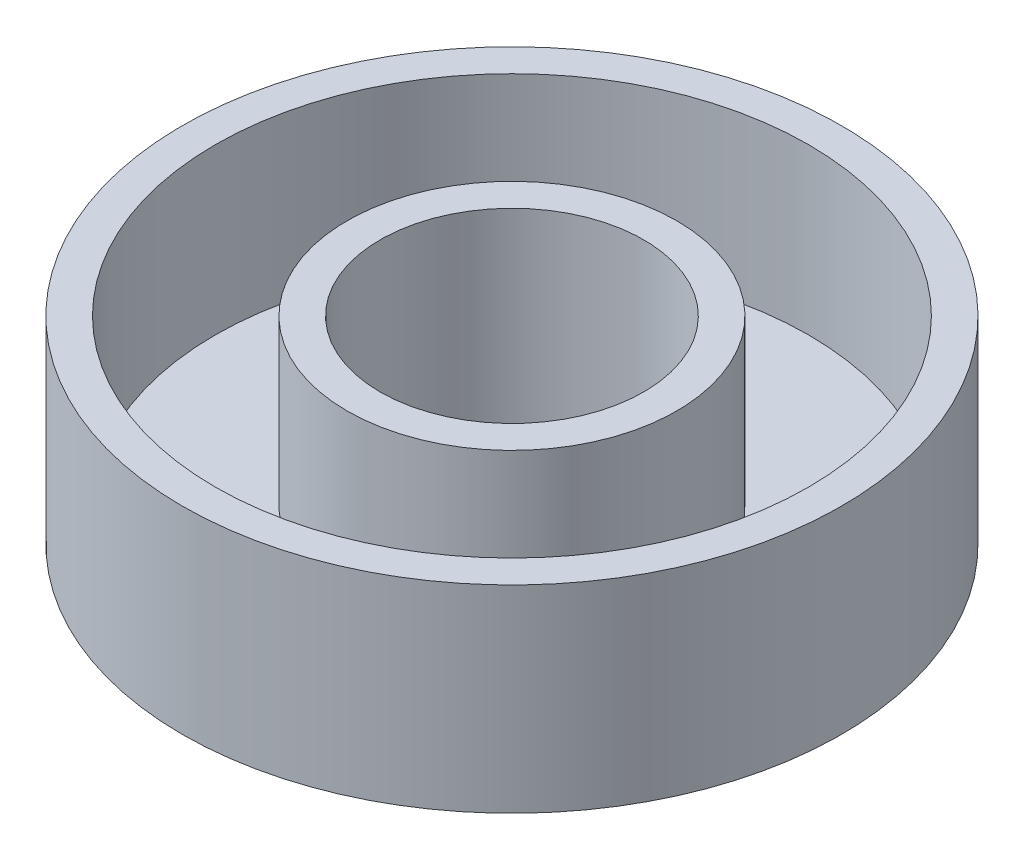
SolidWorks part; units mm, degrees
material "VITON"
ref_plane "Front Plane" through (0, 0, 0) normal (0, 0, 1) x (1, 0, 0)
ref_plane "Top Plane" through (0, 0, 0) normal (0, 1, 0) x (1, 0, 0)
ref_plane "Right Plane" through (0, 0, 0) normal (1, 0, 0) x (0, 0, -1)
sketch "Sketch1" plane through (0, 0, 0) normal (0, 1, 0) x (1, 0, 0)
  circle A0 centre (0, 0) radius 10
  dimension "D1" = 20
extrude "main extrusion" add sketch "Sketch1" along normal blind 6 contours A0
sketch "Sketch2" plane through (0, 6, 0) normal (0, 1, 0) x (1, 0, 0)
  circle A0 centre (0, 0) radius 4
  dimension "D1" = 8
extrude "ID bore" cut sketch "Sketch2" against normal blind 20
sketch "Sketch3" plane through (0, 6, 0) normal (0, 1, 0) x (1, 0, 0)
  circle A0 centre (0, 0) radius 9
  circle A1 centre (0, 0) radius 5
  dimension "D1" = 10
  dimension "D2" = 18
extrude "seal recess" cut sketch "Sketch3" against normal blind 5
equation "\"D1@Sketch1\"=\"seal OD\""
equation "\"D1@main extrusion\" = \"bearing depth\""
equation "\"D1@Sketch2\"=\"seal ID\""
equation "\"bearing OD\" = 20mm"
equation "\"bearing outer race thickness\"= 1mm"
equation "\"bearing ID\"= 10mm"
equation "\"bearing depth\"= 6mm"
equation "\"bearing inner race thickness\"= 1mm"
equation "\"seal OD\" = 20mm"
equation "\"seal ID\"= 8mm"
equation "\"seal depth\"= 6mm"
equation "\"motor to housing distance\"= 60mm"
equation "\"motor mount pattern diameter\"= 30mm"
equation "\"motor mount coupler shaft hole diameter\"= \"coupler shaft base diameter\"+ 4mm"
equation "\"motor mount to housing m8 screw hole diameter\"= 8.5mm"
equation "\"motor mount to housing m8 screw post radius\"= ( 3 * \"motor mount to housing m8 screw hole diameter\" ) / 2"
equation "\"motor mount to housing m8 pattern diameter\"= 100mm"
equation "\"motor mount to housing m4 screw hole diamater\"= 4mm"
equation "\"motor mount to housing m4 head diameter\"= 7.25mm"
equation "\"motor mount to housing m4 head depth\"= 4mm"
equation "\"motor mount plate thickness\"= 6mm + \"motor mount to housing m4 head depth\""
equation "\"motor mount m6 screw hole diameter\"= 6.5mm"
equation "\"motor mount m6 screw socket head diameter\"= 10.5mm"
equation "\"motor mount m6 screw socket head depth\"= 6mm"
equation "\"motor shaft pride\"= 32mm"
equation "\"motor shaft flat section length from tip\"= 25.7mm"
equation "\"motor shaft bore end clearance\"= 2mm"
equation "\"motor mount shaft hole depth\"= \"motor shaft pride\""
equation "\"coupler shaft set screw drill hole diameter\"= 6mm"
equation "\"coupler shaft motor shaft hole diameter\"= 8mm"
equation "\"coupler shaft base diameter\"= 18mm"
equation "\"coupler shaft base length\"= \"motor mount shaft hole depth\" + 10mm"
equation "\"coupler shaft second section diameter\"= \"bearing ID\" + \"bearing inner race thickness\" * 2"
equation "\"coupler shaft third section diamater\"= \"bearing ID\""
equation "\"coupler shaft second section length\"= \"motor to housing distance\" -  \"coupler shaft base length\" - 2mm"
equation "\"coupler shaft set screw 1 distance\"= \"motor mount shaft hole depth\" / 3"
equation "\"coupler shaft set screw 2 distance\"= \"motor mount shaft hole depth\" * 4 / 5"
equation "\"housing bearing seat lip thickness\" = 2mm"
equation "\"housing base thickness\"= \"housing bearing seat lip thickness\" + \"seal depth\" + \"bearing depth\""
equation "\"impeller base outer diameter\"= 1.75in"
equation "\"impeller base outer thickness\"= 1mm"
equation "\"impeller base center thickness\"= 5mm"
equation "\"impeller number of vanes\"= 8"
equation "\"impeller vane outer height`\"= 4mm"
equation "\"impeller vane inner height\"= 8mm"
equation "\"impeller primary vane opening diamater\"= 10mm"
equation "\"impeller shaft bore size\"=4mm "
equation "\"impeller vane inner thickness\"= .75mm"
equation "\"impeller vane outer thickness\"= 1.5mm"
equation "\"impeller primary vane entrance angle\"= 20deg"
equation "\"impeller secondary vane entrance angle\"= 20deg"
equation "\"impeller secondary vane opening diameter\"= 10mm"
equation "\"housing top impeller vertical clearance\"= 1mm"
equation "\"housing top impeller horizontal clearance\"= 1mm"
equation "\"housing top impeller bottom clearance\"= 2mm"
equation "\"housing top impeller cavity height\"= \"housing top impeller bottom clearance\" + \"impeller base center thickness\" + \"impeller vane inner height\" + \"housing top impeller vertical clearance\""
equation "\"housing top impeller cavity diameter\"= 2 * \"housing top impeller horizontal clearance\" + \"impeller base outer diameter\""
equation "\"housing top impeller cavity tip height\"= \"housing top impeller bottom clearance\" + \"housing top impeller vertical clearance\" + \"impeller base outer thickness\" + \"impeller vane outer height\""
equation "\"housing top entrance OD\"= 20mm"
equation "\"housing top exit OD\"= 5mm"
equation "\"housing top o-ring channel height\"= 1.5mm"
equation "\"housing top o ring channel width\"= 1.5mm"
equation "\"housing top threaded inlet depth\"= 8mm"
equation "\"housing top total thickness\"= \"housing top threaded inlet depth\" + \"housing top impeller cavity height\""
equation "\"housing top total width\"= 10mm"
equation "\"housing top exit threaded diameter\"= 8mm"
equation "\"housing top exit threaded depth\"= 8mm"
equation "\"D2@Sketch3\"=\"seal OD\"-2mm"
equation "\"D1@Sketch3\"=\"seal ID\"+2mm"
equation "\"D1@seal recess\"=\"seal depth\"-1mm"
